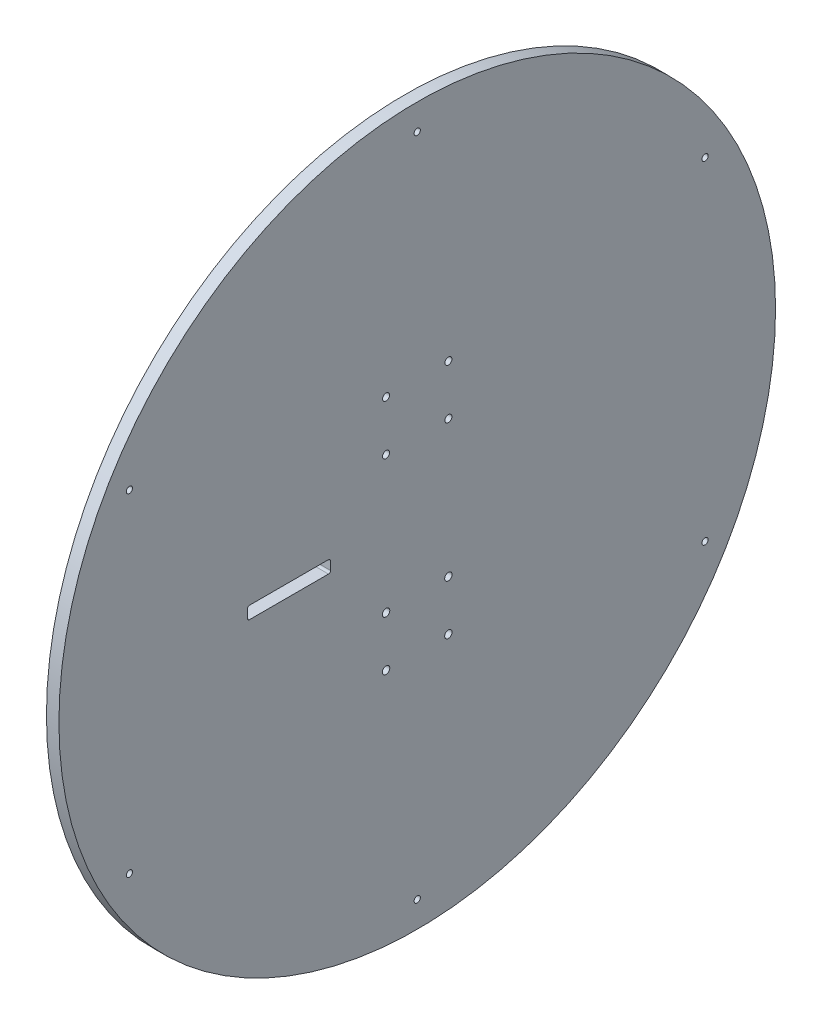
SolidWorks part; units mm, degrees
ref_plane "前视基准面" through (0, 0, 0) normal (0, 0, 1) x (1, 0, 0)
ref_plane "上视基准面" through (0, 0, 0) normal (0, 1, 0) x (1, 0, 0)
ref_plane "右视基准面" through (0, 0, 0) normal (1, 0, 0) x (0, 0, -1)
sketch "草图1" plane through (0, 0, 0) normal (1, 0, 0) x (0, 0, -1)
  line L0 (172.5, 0) -> (-172.5, 0) construction
  line L2 (-42.7306, 3) -> (-80.7306, 3)
  line L3 (-41.7306, 2) -> (-41.7306, -2)
  line L4 (-42.7306, -3) -> (-80.7306, -3)
  line L5 (-81.7306, 2) -> (-81.7306, -2)
  circle A1 centre (-15, -56.9363) radius 1.7858
  circle A2 centre (15, -56.9363) radius 1.7858
  circle A3 centre (15, -32.9363) radius 1.7858
  circle A4 centre (-15, -32.9363) radius 1.7858
  circle A5 centre (-15, 32.9363) radius 1.6897
  circle A6 centre (-15, 56.9363) radius 1.6897
  circle A7 centre (15, 32.9363) radius 1.6897
  circle A8 centre (15, 56.9363) radius 1.6897
  circle A9 centre (0, 0) radius 172.5
  arc A10 (-81.7306, -2) -> (-80.7306, -3) centre (-80.7306, -2) ccw
  arc A11 (-81.7306, 2) -> (-80.7306, 3) centre (-80.7306, 2) cw
  arc A12 (-41.7306, -2) -> (-42.7306, -3) centre (-42.7306, -2) cw
  arc A13 (-42.7306, 3) -> (-41.7306, 2) centre (-42.7306, 2) cw
  circle A14 centre (0, 160) radius 1.5
  circle A15 centre (138.5641, 80) radius 1.5
  circle A16 centre (138.5641, -80) radius 1.5
  circle A17 centre (0, -160) radius 1.5
  circle A18 centre (-138.5641, -80) radius 1.5
  circle A19 centre (-138.5641, 80) radius 1.5
  point P15 (-61.7306, 0)
  point P31 (0, 0)
  point P32 (0, 0)
  dimension "D1" = 1
  dimension "D2" = 6
  dimension "D3" = 160
extrude "凸台-拉伸1" add sketch "草图1" against normal blind 6 contours A9 L0 L3 A12 L4 A10 L5 A4 A3 A2 A1 A16 A17 A18 | L0 A9 L5 A11 L2 A13 L3 A19 A15 A14 A5 A6 A7 A8
